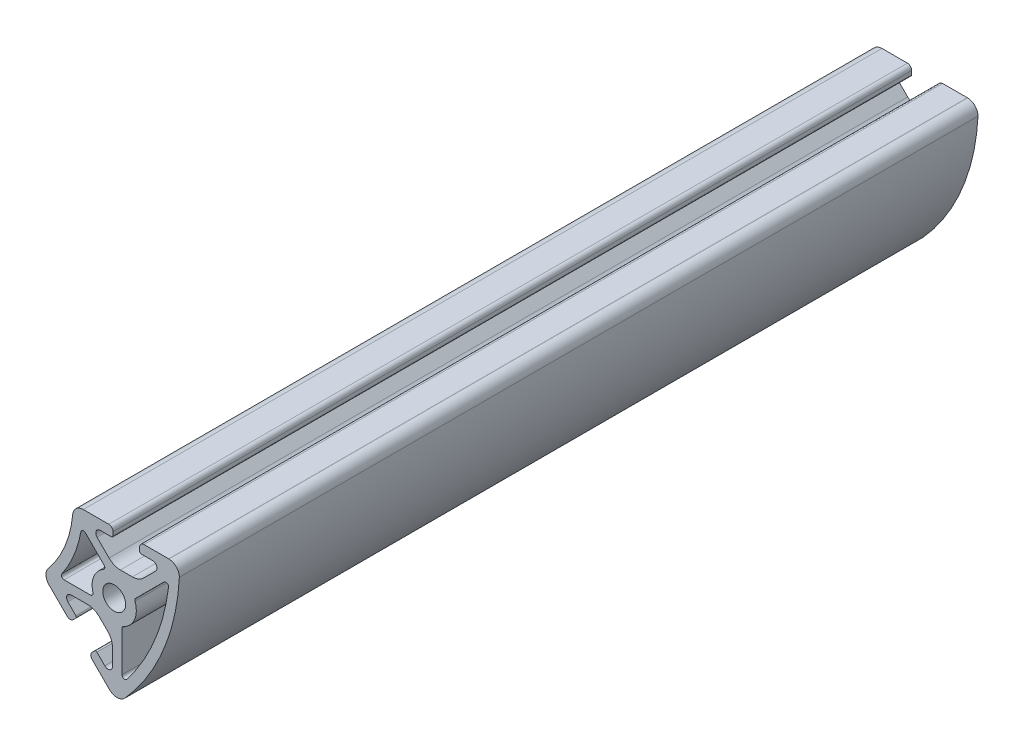
SolidWorks part; units mm, degrees
ref_plane "Front Plane" through (0, 0, 0) normal (0, 0, 1) x (1, 0, 0)
ref_plane "Top Plane" through (0, 0, 0) normal (0, 1, 0) x (1, 0, 0)
ref_plane "Right Plane" through (0, 0, 0) normal (1, 0, 0) x (0, 0, -1)
sketch "Sketch1" plane through (0, 0, 0) normal (0, 0, 1) x (1, 0, 0)
  line L0 (-12.1437, 13.1178) -> (-15.6366, 16.6108)
  line L1 (-19.64, 6.9458) -> (-14.7002, 6.9458)
  line L2 (-0.8709, 15.9853) -> (-6.2076, 10.6486)
  line L3 (-8.7567, 4.4944) -> (-8.7567, -3.0528)
  line L4 (-17.9338, 1.3105) -> (-17.4389, 1.8054)
  line L5 (-17.4389, 2.2297) -> (-18.9362, 3.7271)
  line L6 (-18.3476, 5.1481) -> (-15.1652, 5.1481)
  line L7 (-13.0439, 4.2694) -> (-11.4394, 2.6649)
  line L8 (-10.5607, 0.5436) -> (-10.5607, -2.6388)
  line L9 (-11.9817, -3.2274) -> (-13.4791, -1.7301)
  line L10 (-13.9033, -1.7301) -> (-14.3983, -2.2251)
  line L11 (-14.3983, -3.3564) -> (-11.0914, -6.6633)
  line L12 (-11.0914, -6.6633) -> (-11.0217, -6.7266)
  line L13 (0.0056, 20.187) -> (-4.6418, 20.187)
  line L14 (-5.4418, 19.387) -> (-5.4418, 18.687)
  line L15 (-5.1418, 18.387) -> (-3.0242, 18.387)
  line L16 (-2.4356, 16.966) -> (-4.6859, 14.7157)
  line L17 (-6.8072, 13.837) -> (-9.0763, 13.837)
  line L18 (-11.1977, 14.7157) -> (-13.448, 16.966)
  line L19 (-12.8594, 18.387) -> (-10.7418, 18.387)
  line L20 (-10.4418, 18.687) -> (-10.4418, 19.387)
  line L21 (-11.2418, 20.187) -> (-16.0329, 20.187)
  line L22 (-22.5571, 4.8111) -> (-22.4177, 4.6629)
  line L23 (-22.4177, 4.6629) -> (-19.0652, 1.3105)
  arc A0 (-20.0503, 7.7315) -> (-19.64, 6.9458) centre (-19.64, 7.4458) ccw
  arc A1 (-20.0503, 7.7315) -> (-16.4823, 16.3453) centre (-37.941, 20.1879) ccw
  arc A2 (-15.6366, 16.6108) -> (-16.4823, 16.3453) centre (-15.9902, 16.2572) ccw
  arc A3 (-12.2528, 12.328) -> (-12.1437, 13.1178) centre (-12.4972, 12.7643) ccw
  arc A4 (-12.2528, 12.328) -> (-14.2189, 7.5815) centre (-10.2246, 8.7074) ccw
  arc A5 (-19.0652, 1.3105) -> (-17.9338, 1.3105) centre (-18.4995, 1.8762) ccw
  arc A6 (-17.4389, 1.8054) -> (-17.4389, 2.2297) centre (-17.651, 2.0176) ccw
  arc A7 (-18.3476, 5.1481) -> (-18.9362, 3.7271) centre (-18.3476, 4.3157) ccw
  arc A8 (-13.0439, 4.2694) -> (-15.1652, 5.1481) centre (-15.1652, 2.1481) ccw
  arc A9 (-10.5607, 0.5436) -> (-11.4394, 2.6649) centre (-13.5607, 0.5436) ccw
  arc A10 (-11.9817, -3.2274) -> (-10.5607, -2.6388) centre (-11.3931, -2.6388) ccw
  arc A11 (-13.4791, -1.7301) -> (-13.9033, -1.7301) centre (-13.6912, -1.9422) ccw
  arc A12 (-14.3983, -2.2251) -> (-14.3983, -3.3564) centre (-13.8326, -2.7907) ccw
  arc A13 (-11.0217, -6.7266) -> (-8.2822, -6.6515) centre (-9.6918, -5.2328) ccw
  arc A14 (-8.2822, -6.6515) -> (2.0085, 18.1922) centre (-37.9418, 20.187) ccw
  arc A15 (2.0085, 18.1922) -> (0.0664, 20.185) centre (0.0085, 18.1858) ccw
  arc A16 (0.0664, 20.185) -> (0.0056, 20.187) centre (-0.0147, 18.6782) ccw
  arc A17 (-4.6418, 20.187) -> (-5.4418, 19.387) centre (-4.6418, 19.387) ccw
  arc A18 (-5.4418, 18.687) -> (-5.1418, 18.387) centre (-5.1418, 18.687) ccw
  arc A19 (-2.4356, 16.966) -> (-3.0242, 18.387) centre (-3.0242, 17.5546) ccw
  arc A20 (-6.8072, 13.837) -> (-4.6859, 14.7157) centre (-6.8072, 16.837) ccw
  arc A21 (-11.1977, 14.7157) -> (-9.0763, 13.837) centre (-9.0763, 16.837) ccw
  arc A22 (-12.8594, 18.387) -> (-13.448, 16.966) centre (-12.8594, 17.5546) ccw
  arc A23 (-10.7418, 18.387) -> (-10.4418, 18.687) centre (-10.7418, 18.687) ccw
  arc A24 (-10.4418, 19.387) -> (-11.2418, 20.187) centre (-11.2418, 19.387) ccw
  arc A25 (-16.0329, 20.187) -> (-18.0246, 18.3688) centre (-16.0329, 18.187) ccw
  arc A26 (-22.5725, 7.3891) -> (-18.0246, 18.3688) centre (-37.9418, 20.187) ccw
  arc A27 (-22.5725, 7.3891) -> (-22.5571, 4.8111) centre (-21.0356, 6.1093) ccw
  arc A28 (-14.7002, 6.9458) -> (-14.2189, 7.5815) centre (-14.7002, 7.4458) ccw
  arc A29 (-12.3754, 8.7065) -> (-8.0754, 8.7065) centre (-10.2254, 8.7065) ccw
  arc A30 (-8.0754, 8.7065) -> (-12.3754, 8.7065) centre (-10.2254, 8.7065) ccw
  arc A31 (-8.4683, 4.9474) -> (-6.324, 10.1243) centre (-10.2246, 8.7074) ccw
  arc A32 (-6.2076, 10.6486) -> (-6.324, 10.1243) centre (-5.854, 10.295) ccw
  arc A33 (-0.021, 15.5713) -> (-0.8709, 15.9853) centre (-0.5173, 15.6317) ccw
  arc A34 (-7.863, -3.3611) -> (-0.021, 15.5713) centre (-37.941, 20.1879) ccw
  arc A35 (-8.7567, -3.0528) -> (-7.863, -3.3611) centre (-8.2567, -3.0528) ccw
  arc A36 (-8.4683, 4.9474) -> (-8.7567, 4.4944) centre (-8.2567, 4.4944) ccw
extrude "Boss-Extrude1" add sketch "Sketch1" along normal blind 150
